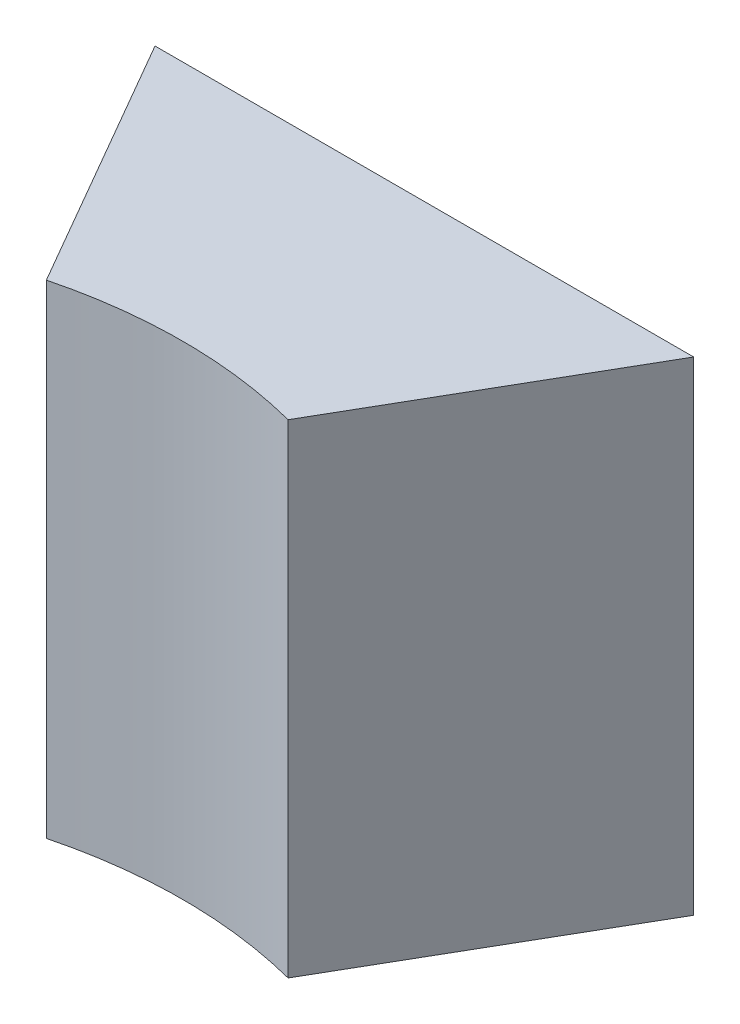
SolidWorks part; units mm, degrees
ref_plane "Ön Düzlem" through (0, 0, 0) normal (0, 0, 1) x (1, 0, 0)
ref_plane "Üst Düzlem" through (0, 0, 0) normal (0, 1, 0) x (1, 0, 0)
ref_plane "Sağ Düzlem" through (0, 0, 0) normal (1, 0, 0) x (0, 0, -1)
sketch "Çizim1" plane through (0, 0, 0) normal (0, 1, 0) x (1, 0, 0)
  line L0 (55.7008, 150) -> (25, 96.8246)
  line L1 (55.7008, 150) -> (-55.7008, 150)
  line L2 (-55.7008, 150) -> (-25, 96.8246)
  arc A0 (25, 96.8246) -> (-25, 96.8246) centre (0, 0) ccw
  point P5 (0, 0)
  dimension "D1" = 200
  dimension "D2" = 150
  dimension "D3" = 60
  dimension "D4" = 50
extrude "Yükseklik-Ekstrüzyon1" add sketch "Çizim1" along normal blind 100
sketch "Çizim2" plane through (0, 100, 0) normal (0, 1, 0) x (1, 0, 0)
  line L0 (-50.5047, 147) -> (50.5047, 147)
  line L1 (50.5047, 147) -> (22.4019, 98.3246)
  line L2 (22.4019, 98.3246) -> (25, 96.8246)
  line L3 (25, 96.8246) -> (55.7008, 150) construction
  line L4 (-25, 96.8246) -> (-22.4019, 98.3246)
  line L5 (-22.4019, 98.3246) -> (-50.5047, 147)
  line L6 (-55.7008, 150) -> (-25, 96.8246) construction
  line L7 (55.7008, 150) -> (-55.7008, 150) construction
  point P11 (0, 0)
  point P12 (0, 0)
  dimension "D1" = 3
  dimension "D2" = 3
